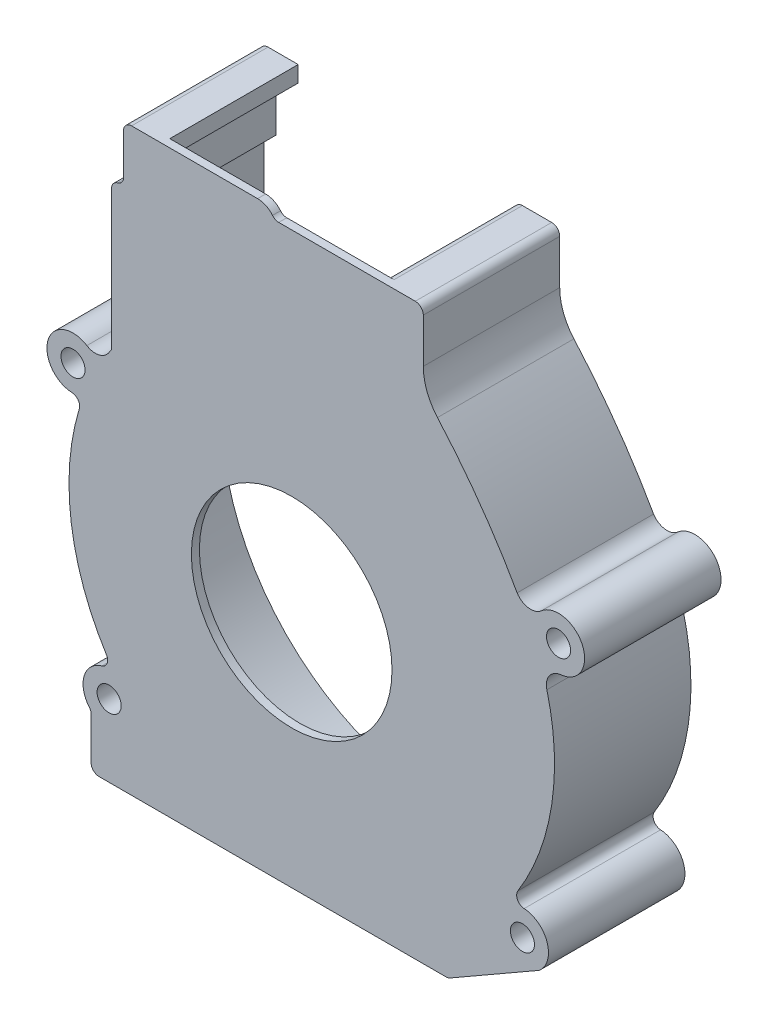
SolidWorks part; units mm, degrees
ref_plane "Front Plane" through (0, 0, 0) normal (0, 0, 1) x (1, 0, 0)
ref_plane "Top Plane" through (0, 0, 0) normal (0, 1, 0) x (1, 0, 0)
ref_plane "Right Plane" through (0, 0, 0) normal (1, 0, 0) x (0, 0, -1)
sketch "Sketch1" plane through (0, 0, 0) normal (0, 0, 1) x (1, 0, 0)
  line L0 (0, 0) -> (-5, 0) construction
  line L1 (-5, 0) -> (-5, 26.5) construction
  line L2 (-5, 26.5) -> (-5, 82.5) construction
  line L3 (-5, 26.5) -> (-59.5, 26.5) construction
  line L4 (-5, 26.5) -> (61.5, 26.5) construction
  line L5 (-5, 0) -> (-5, -41.5) construction
  line L6 (-5, -41.5) -> (-50.5, -41.5) construction
  line L7 (-5, -41.5) -> (52.5, -41.5) construction
  line L8 (-5, -41.5) -> (-5, -59.5) construction
  line L9 (-5, -59.5) -> (33.4669, -59.5)
  line L10 (34.4624, -59.2347) -> (56.6538, -46.4996)
  line L11 (-5, -59.5) -> (-53, -59.5)
  line L12 (-55, -57.5) -> (-55, -46.9772)
  line L13 (-49.8999, 69) -> (-49.8999, 34.2089)
  line L14 (-47.8999, 71) -> (-46.8999, 71)
  line L15 (-49.8999, 26.5) -> (-49.8999, 71) construction
  line L16 (-46.8999, 71) -> (-46.8999, 83)
  line L17 (-44.8999, 85) -> (-13.5, 85)
  line L18 (-5, 82.5) -> (-9.2869, 82.5) construction
  line L19 (-5, 82.5) -> (-3.5, 82.5)
  line L20 (-3.5, 82.5) -> (-3.5, 78.5)
  line L21 (-3.5, 78.5) -> (-5, 78.5)
  line L22 (-3.5, 82.5) -> (16.5, 82.5) construction
  line L23 (16.5, 80.5) -> (16.5, 78.5)
  line L24 (18.5, 82.5) -> (25.8, 82.5)
  line L25 (27.8, 80.5) -> (27.8, 69.4429)
  line L26 (0, 0) -> (51.1848, 32.2548) construction
  line L27 (16.5, 78.5) -> (21.8, 78.5)
  line L28 (23.8, 76.5) -> (23.8, 66.8106)
  line L29 (-8.2322, 82.5) -> (-5, 82.5)
  line L30 (-5, 80.2) -> (-23.0787, 80.2) construction
  line L31 (-13.5, 85) -> (-13.5, 76.5) construction
  line L32 (-40.8999, 81) -> (-20.1933, 81)
  line L33 (-42.8999, 79) -> (-42.8999, 67)
  line L34 (-42.8999, 67) -> (-43.8999, 67)
  line L35 (-45.8999, 65) -> (-45.8999, 46.8172)
  line L36 (-5, 78.5) -> (-7.7947, 78.5)
  line L37 (-5, 46.2) -> (-32.524, 46.2) construction
  arc A0 (-39.1968, 40.6922) -> (47.8006, 30.1222) centre (0, 0) ccw
  circle A1 centre (52.5, -41.5) radius 3
  arc A3 (51.3679, -31.9623) -> (58.5982, 15.0501) centre (0, 0) ccw
  circle A4 centre (0, 0) radius 60.5 construction
  circle A5 centre (-50.5, -41.5) radius 3
  arc A6 (-52.3102, -35.2572) -> (-55.4706, -45.6885) centre (-50.5, -41.5) ccw
  arc A7 (-44.0227, -41.5) -> (-44, -41.524) centre (0, 0) ccw
  circle A8 centre (-59.5, 26.5) radius 3
  arc A9 (-44, -41.524) -> (-44, -41.5) centre (-50.5, -41.5) ccw
  arc A10 (54.721, -47.6088) -> (52.9329, -35.0144) centre (52.5, -41.5) ccw
  circle A11 centre (61.5, 26.5) radius 3
  arc A12 (-56.0461, 32.0064) -> (-59.7674, 20.0055) centre (-59.5, 26.5) ccw
  arc A13 (62.102, 20.0279) -> (57.2093, 31.3826) centre (61.5, 26.5) ccw
  arc A14 (-57.9345, 17.431) -> (-51.1755, -32.2695) centre (0, 0) ccw
  arc A15 (-38.5261, 46.6475) -> (-37.3763, 48.2045) centre (-41.0733, 49.7317) ccw
  arc A16 (-52.3102, -35.2572) -> (-51.1755, -32.2695) centre (-52.8672, -33.3363) ccw
  arc A17 (-55, -46.9772) -> (-55.4706, -45.6885) centre (-57, -46.9772) ccw
  arc A18 (-53, -59.5) -> (-55, -57.5) centre (-53, -57.5) cw
  arc A19 (33.4669, -59.5) -> (34.4624, -59.2347) centre (33.4669, -57.5) ccw
  arc A20 (52.9329, -35.0144) -> (51.3679, -31.9623) centre (53.066, -33.0189) cw
  arc A21 (-57.9345, 17.431) -> (-59.7674, 20.0055) centre (-59.8497, 18.0072) ccw
  arc A22 (62.102, 20.0279) -> (58.5982, 15.0501) centre (62.4724, 16.0451) ccw
  arc A23 (57.2093, 31.3826) -> (51.1848, 32.2548) centre (54.5689, 34.3873) cw
  arc A24 (-50.5768, 33.2) -> (-56.0461, 32.0064) centre (-53.9207, 35.395) cw
  arc A25 (31.3271, 60.1522) -> (51.1848, 32.2548) centre (-88.5559, -46.1979) cw
  arc A26 (27.5522, 57.2722) -> (33.7188, 50.2324) centre (-85.9348, -48.3593) cw
  arc A27 (31.3271, 60.1522) -> (27.8, 69.4429) centre (41.8, 69.4429) cw
  arc A28 (27.5522, 57.2722) -> (23.8, 66.8106) centre (37.8, 66.8106) cw
  arc A29 (16.5, 80.5) -> (18.5, 82.5) centre (18.5, 80.5) cw
  arc A30 (23.8, 76.5) -> (21.8, 78.5) centre (21.8, 76.5) ccw
  arc A31 (27.8, 80.5) -> (25.8, 82.5) centre (25.8, 80.5) ccw
  arc A32 (-18.2247, 79.3529) -> (-9.4728, 77.5882) centre (-13.5, 80.2) ccw
  circle A33 centre (-13.5, 80.2) radius 3
  arc A34 (-46.8999, 83) -> (-44.8999, 85) centre (-44.8999, 83) cw
  arc A35 (-42.8999, 79) -> (-40.8999, 81) centre (-40.8999, 79) cw
  arc A36 (-45.8999, 65) -> (-43.8999, 67) centre (-43.8999, 65) cw
  arc A37 (-49.8999, 69) -> (-47.8999, 71) centre (-47.8999, 69) cw
  arc A38 (-18.2247, 79.3529) -> (-20.1933, 81) centre (-20.1933, 79) ccw
  arc A39 (-9.7815, 83.2353) -> (-13.5, 85) centre (-13.5, 80.2) ccw
  arc A40 (-9.7815, 83.2353) -> (-8.2322, 82.5) centre (-8.2322, 84.5) ccw
  arc A41 (-9.4728, 77.5882) -> (-7.7947, 78.5) centre (-7.7947, 76.5) cw
  circle A42 centre (-32.524, 46.2) radius 3
  arc A43 (-34.7363, 41.4389) -> (-37.3763, 48.2045) centre (-32.524, 46.2) ccw
  circle A44 centre (0, 0) radius 56.5 construction
  arc A45 (-38.5261, 46.6475) -> (-40.8731, 44.6053) centre (0, 0) ccw
  arc A46 (33.7188, 50.2324) -> (47.8006, 30.1222) centre (-33.6599, -11.9339) cw
  arc A47 (-39.1968, 40.6922) -> (-34.7363, 41.4389) centre (-36.4218, 37.8114) cw
  arc A48 (-49.8999, 34.2089) -> (-50.5768, 33.2) centre (0, 0) ccw
  arc A49 (-45.8999, 46.8172) -> (-40.8731, 44.6053) centre (-42.8999, 46.8172) ccw
  circle A50 centre (-5, 0) radius 45 construction
  point P80 (27.8, 82.5)
  point P94 (-46.8999, 85)
  dimension "D1" = 113
  dimension "D5" = 45.5
  dimension "D7" = 4
  dimension "D8" = 2
  dimension "D9" = 2
  dimension "D18" = 4
  dimension "D19" = 4
  dimension "D20" = 4
  dimension "D22" = 14
  dimension "D23" = 2
  dimension "D26" = 4
  dimension "D13" = 4
  dimension "D29" = 2
  dimension "D30" = 2
  dimension "D31" = 2
  dimension "D33" = 4
  dimension "D34" = 3
  dimension "D2" = 5
  dimension "D3" = 26.5
  dimension "D4" = 56
  dimension "D6" = 57.5
  dimension "D10" = 44.5
  dimension "D11" = 14
  dimension "D12" = 3
  dimension "D14" = 1.5
  dimension "D15" = 4
  dimension "D16" = 20
  dimension "D17" = 11.3
  dimension "D21" = 4
  dimension "D24" = 2.3
  dimension "D25" = 8.5
  dimension "D27" = 4
  dimension "D28" = 4
  dimension "D32" = 19.7
extrude "Boss-Extrude1" add sketch "Sketch1" along normal blind 32 contours A49 L35 A36 L34 L33 A35 L32 A38 A32 A41 L36 L21 L20 L19 L29 A40 A39 L17 A34 L16 L14 A37 L13 A48 A24 A12 A21 A14 A16 A6 A17 L12 A18 L11 L9 A19 L10 A10 A20 A3 A22 A13 A23 A25 A27 L25 A31 L24 A29 L23
sketch "Sketch2" plane through (0, 0, 32) normal (0, 0, 1) x (1, 0, 0)
  line L0 (-3.5, 82.5) -> (18.5, 82.5)
  line L1 (-3.5, 82.5) -> (16.5, 82.5) construction
  line L19 (-45.8999, 46.8172) -> (-45.8999, 65)
  line L20 (-43.8999, 67) -> (-42.8999, 67)
  line L21 (-42.8999, 67) -> (-42.8999, 79)
  line L22 (-40.8999, 81) -> (-20.1933, 81)
  line L23 (-7.7947, 78.5) -> (-3.5, 78.5)
  line L24 (-3.5, 78.5) -> (-3.5, 82.5)
  line L25 (-3.5, 82.5) -> (-8.2322, 82.5)
  line L26 (-13.5, 85) -> (-44.8999, 85)
  line L27 (-46.8999, 83) -> (-46.8999, 71)
  line L28 (-46.8999, 71) -> (-47.8999, 71)
  line L29 (-49.8999, 69) -> (-49.8999, 34.2089)
  line L30 (-55, -46.9772) -> (-55, -57.5)
  line L31 (-53, -59.5) -> (33.4669, -59.5)
  line L32 (34.4624, -59.2347) -> (56.6538, -46.4996)
  line L33 (27.8, 69.4429) -> (27.8, 80.5)
  line L34 (25.8, 82.5) -> (18.5, 82.5)
  line L35 (16.5, 80.5) -> (16.5, 78.5)
  line L36 (16.5, 78.5) -> (21.8, 78.5)
  line L37 (23.8, 76.5) -> (23.8, 66.8106)
  line L44 (-3.5, 82.5) -> (-8.2322, 82.5)
  line L45 (-13.5, 85) -> (-44.8999, 85)
  line L46 (-46.8999, 83) -> (-46.8999, 71)
  line L47 (-46.8999, 71) -> (-47.8999, 71)
  line L48 (-49.8999, 69) -> (-49.8999, 34.2089)
  line L49 (-55, -46.9772) -> (-55, -57.5)
  line L50 (-53, -59.5) -> (33.4669, -59.5)
  line L51 (34.4624, -59.2347) -> (56.6538, -46.4996)
  line L52 (27.8, 69.4429) -> (27.8, 80.5)
  line L53 (25.8, 82.5) -> (18.5, 82.5)
  circle A0 centre (61.5, 26.5) radius 3 construction
  circle A1 centre (61.5, 26.5) radius 3
  circle A2 centre (52.5, -41.5) radius 3 construction
  circle A3 centre (-50.5, -41.5) radius 3 construction
  circle A4 centre (-59.5, 26.5) radius 3 construction
  circle A5 centre (-32.524, 46.2) radius 3 construction
  circle A6 centre (-13.5, 80.2) radius 3 construction
  circle A7 centre (52.5, -41.5) radius 3
  circle A8 centre (-50.5, -41.5) radius 3
  circle A9 centre (-59.5, 26.5) radius 3
  circle A10 centre (-32.524, 46.2) radius 3
  circle A11 centre (-13.5, 80.2) radius 3
  circle A12 centre (-5, 0) radius 25
  arc A39 (-45.8999, 46.8172) -> (-40.8731, 44.6053) centre (-42.8999, 46.8172) ccw
  arc A40 (-43.8999, 67) -> (-45.8999, 65) centre (-43.8999, 65) ccw
  arc A41 (-40.8999, 81) -> (-42.8999, 79) centre (-40.8999, 79) ccw
  arc A42 (-18.2247, 79.3529) -> (-20.1933, 81) centre (-20.1933, 79) ccw
  arc A43 (-18.2247, 79.3529) -> (-9.4728, 77.5882) centre (-13.5, 80.2) ccw
  arc A44 (-7.7947, 78.5) -> (-9.4728, 77.5882) centre (-7.7947, 76.5) ccw
  arc A45 (-9.7815, 83.2353) -> (-8.2322, 82.5) centre (-8.2322, 84.5) ccw
  arc A46 (-9.7815, 83.2353) -> (-13.5, 85) centre (-13.5, 80.2) ccw
  arc A47 (-44.8999, 85) -> (-46.8999, 83) centre (-44.8999, 83) ccw
  arc A48 (-47.8999, 71) -> (-49.8999, 69) centre (-47.8999, 69) ccw
  arc A49 (-49.8999, 34.2089) -> (-50.5768, 33.2) centre (0, 0) ccw
  arc A50 (-56.0461, 32.0064) -> (-50.5768, 33.2) centre (-53.9207, 35.395) ccw
  arc A51 (-56.0461, 32.0064) -> (-59.7674, 20.0055) centre (-59.5, 26.5) ccw
  arc A52 (-57.9345, 17.431) -> (-59.7674, 20.0055) centre (-59.8497, 18.0072) ccw
  arc A53 (-57.9345, 17.431) -> (-51.1755, -32.2695) centre (0, 0) ccw
  arc A54 (-52.3102, -35.2572) -> (-51.1755, -32.2695) centre (-52.8672, -33.3363) ccw
  arc A55 (-52.3102, -35.2572) -> (-55.4706, -45.6885) centre (-50.5, -41.5) ccw
  arc A56 (-55, -46.9772) -> (-55.4706, -45.6885) centre (-57, -46.9772) ccw
  arc A57 (-55, -57.5) -> (-53, -59.5) centre (-53, -57.5) ccw
  arc A58 (33.4669, -59.5) -> (34.4624, -59.2347) centre (33.4669, -57.5) ccw
  arc A59 (56.6538, -46.4996) -> (52.9329, -35.0144) centre (52.5, -41.5) ccw
  arc A60 (51.3679, -31.9623) -> (52.9329, -35.0144) centre (53.066, -33.0189) ccw
  arc A61 (51.3679, -31.9623) -> (58.5982, 15.0501) centre (0, 0) ccw
  arc A62 (62.102, 20.0279) -> (58.5982, 15.0501) centre (62.4724, 16.0451) ccw
  arc A63 (62.102, 20.0279) -> (57.2093, 31.3826) centre (61.5, 26.5) ccw
  arc A64 (51.1848, 32.2548) -> (57.2093, 31.3826) centre (54.5689, 34.3873) ccw
  arc A65 (51.1848, 32.2548) -> (31.3271, 60.1522) centre (-88.5559, -46.1979) ccw
  arc A66 (27.8, 69.4429) -> (31.3271, 60.1522) centre (41.8, 69.4429) ccw
  arc A67 (27.8, 80.5) -> (25.8, 82.5) centre (25.8, 80.5) ccw
  arc A68 (18.5, 82.5) -> (16.5, 80.5) centre (18.5, 80.5) ccw
  arc A69 (23.8, 76.5) -> (21.8, 78.5) centre (21.8, 76.5) ccw
  arc A70 (23.8, 66.8106) -> (27.5522, 57.2722) centre (37.8, 66.8106) ccw
  arc A71 (33.7188, 50.2324) -> (27.5522, 57.2722) centre (-85.9348, -48.3593) ccw
  arc A72 (47.8006, 30.1222) -> (33.7188, 50.2324) centre (-33.6599, -11.9339) ccw
  arc A73 (-39.1968, 40.6922) -> (47.8006, 30.1222) centre (0, 0) ccw
  arc A74 (-34.7363, 41.4389) -> (-39.1968, 40.6922) centre (-36.4218, 37.8114) ccw
  arc A75 (-34.7363, 41.4389) -> (-37.3763, 48.2045) centre (-32.524, 46.2) ccw
  arc A76 (-38.5261, 46.6475) -> (-37.3763, 48.2045) centre (-41.0733, 49.7317) ccw
  arc A77 (-38.5261, 46.6475) -> (-40.8731, 44.6053) centre (0, 0) ccw
  arc A84 (-9.7815, 83.2353) -> (-8.2322, 82.5) centre (-8.2322, 84.5) ccw
  arc A85 (-9.7815, 83.2353) -> (-13.5, 85) centre (-13.5, 80.2) ccw
  arc A86 (-44.8999, 85) -> (-46.8999, 83) centre (-44.8999, 83) ccw
  arc A87 (-47.8999, 71) -> (-49.8999, 69) centre (-47.8999, 69) ccw
  arc A88 (-49.8999, 34.2089) -> (-50.5768, 33.2) centre (0, 0) ccw
  arc A89 (-56.0461, 32.0064) -> (-50.5768, 33.2) centre (-53.9207, 35.395) ccw
  arc A90 (-56.0461, 32.0064) -> (-59.7674, 20.0055) centre (-59.5, 26.5) ccw
  arc A91 (-57.9345, 17.431) -> (-59.7674, 20.0055) centre (-59.8497, 18.0072) ccw
  arc A92 (-57.9345, 17.431) -> (-51.1755, -32.2695) centre (0, 0) ccw
  arc A93 (-52.3102, -35.2572) -> (-51.1755, -32.2695) centre (-52.8672, -33.3363) ccw
  arc A94 (-52.3102, -35.2572) -> (-55.4706, -45.6885) centre (-50.5, -41.5) ccw
  arc A95 (-55, -46.9772) -> (-55.4706, -45.6885) centre (-57, -46.9772) ccw
  arc A96 (-55, -57.5) -> (-53, -59.5) centre (-53, -57.5) ccw
  arc A97 (33.4669, -59.5) -> (34.4624, -59.2347) centre (33.4669, -57.5) ccw
  arc A98 (56.6538, -46.4996) -> (52.9329, -35.0144) centre (52.5, -41.5) ccw
  arc A99 (51.3679, -31.9623) -> (52.9329, -35.0144) centre (53.066, -33.0189) ccw
  arc A100 (51.3679, -31.9623) -> (58.5982, 15.0501) centre (0, 0) ccw
  arc A101 (62.102, 20.0279) -> (58.5982, 15.0501) centre (62.4724, 16.0451) ccw
  arc A102 (62.102, 20.0279) -> (57.2093, 31.3826) centre (61.5, 26.5) ccw
  arc A103 (51.1848, 32.2548) -> (57.2093, 31.3826) centre (54.5689, 34.3873) ccw
  arc A104 (51.1848, 32.2548) -> (31.3271, 60.1522) centre (-88.5559, -46.1979) ccw
  arc A105 (27.8, 69.4429) -> (31.3271, 60.1522) centre (41.8, 69.4429) ccw
  arc A106 (27.8, 80.5) -> (25.8, 82.5) centre (25.8, 80.5) ccw
  arc A115 (-38.5261, 46.6475) -> (-37.3763, 48.2045) centre (-41.0733, 49.7317) ccw
  dimension "D1" = 0
extrude "Boss-Extrude2" add sketch "Sketch2" along normal blind 2
sketch "Sketch3" plane through (0, 0, 34) normal (0, 0, 1) x (1, 0, 0)
  line L0 (-3.5, 82.5) -> (16.5, 82.5) construction
  line L1 (-5, 82.5) -> (-3.5, 82.5) construction
  line L2 (-8.2322, 82.5) -> (-5, 82.5) construction
  line L3 (-44.8999, 85) -> (-13.5, 85) construction
  line L7 (-3.5, 82.5) -> (16.5, 82.5)
  line L8 (-5, 82.5) -> (-3.5, 82.5)
  line L9 (-8.2322, 82.5) -> (-5, 82.5)
  line L10 (-37.3763, 85) -> (-13.5, 85)
  line L14 (16.5, 82.5) -> (16.5, 46.4817)
  line L15 (13.5184, 43.4817) -> (-22.5293, 43.2611)
  line L16 (-40.8483, 43.8791) -> (-45.8999, 48.1905)
  line L17 (-40.8999, 81) -> (-20.1933, 81) construction
  line L18 (-42.8999, 79) -> (-42.8999, 67) construction
  line L19 (-42.8999, 67) -> (-43.8999, 67) construction
  line L20 (-45.8999, 65) -> (-45.8999, 46.8172) construction
  line L21 (-40.8999, 81) -> (-37.3763, 81)
  line L22 (-42.8999, 79) -> (-42.8999, 67)
  line L23 (-42.8999, 67) -> (-43.8999, 67)
  line L24 (-45.8999, 65) -> (-45.8999, 48.1905)
  line L25 (-37.3763, 81) -> (-37.3763, 85)
  arc A0 (-9.7815, 83.2353) -> (-8.2322, 82.5) centre (-8.2322, 84.5) ccw construction
  arc A1 (-9.7815, 83.2353) -> (-13.5, 85) centre (-13.5, 80.2) ccw construction
  arc A4 (-9.7815, 83.2353) -> (-8.2322, 82.5) centre (-8.2322, 84.5) ccw
  arc A5 (-9.7815, 83.2353) -> (-13.5, 85) centre (-13.5, 80.2) ccw
  arc A10 (16.5, 46.4817) -> (13.5184, 43.4817) centre (13.5, 46.4817) cw
  arc A11 (-40.8483, 43.8791) -> (-25.0912, 41.7916) centre (-32.524, 46.2) ccw
  arc A12 (-25.0912, 41.7916) -> (-22.5293, 43.2611) centre (-22.5109, 40.2612) cw
  arc A13 (-40.8999, 81) -> (-42.8999, 79) centre (-40.8999, 79) ccw construction
  arc A14 (-43.8999, 67) -> (-45.8999, 65) centre (-43.8999, 65) ccw construction
  arc A15 (-40.8999, 81) -> (-42.8999, 79) centre (-40.8999, 79) ccw
  arc A16 (-43.8999, 67) -> (-45.8999, 65) centre (-43.8999, 65) ccw
  point P20 (-39.9989, 43.1542)
  point P26 (16.5, 43.5)
  point P30 (-42.8999, 67)
  point P32 (-43.8999, 67)
  dimension "D4" = 3
  dimension "D1" = 39
  dimension "D2" = 56.4989
extrude "Cut-Extrude3" cut sketch "Sketch3" against normal blind 43.5
sketch "Sketch5" plane through (0, 0, 34) normal (0, 0, 1) x (1, 0, 0)
  line L0 (-3.5, 82.5) -> (16.5, 82.5) construction
  line L1 (-5, 82.5) -> (-3.5, 82.5) construction
  line L2 (-8.2322, 82.5) -> (-5, 82.5) construction
  line L3 (-44.8999, 85) -> (-13.5, 85) construction
  line L4 (-40.8999, 81) -> (-20.1933, 81) construction
  line L5 (16.5, 46.4817) -> (16.5, 82.5) construction
  line L6 (-22.5293, 43.2611) -> (13.5184, 43.4817) construction
  line L7 (-45.8999, 48.1905) -> (-40.8483, 43.8791) construction
  line L8 (-45.8999, 65) -> (-45.8999, 46.8172) construction
  line L9 (-42.8999, 67) -> (-43.8999, 67) construction
  line L10 (-42.8999, 79) -> (-42.8999, 67) construction
  line L11 (-37.3763, 85) -> (-37.3763, 81) construction
  line L12 (-3.5, 82.5) -> (16.5, 82.5)
  line L13 (-5, 82.5) -> (-3.5, 82.5)
  line L14 (-8.2322, 82.5) -> (-5, 82.5)
  line L15 (-37.3763, 85) -> (-13.5, 85)
  line L16 (-40.8999, 81) -> (-37.3763, 81)
  line L17 (16.5, 46.4817) -> (16.5, 82.5)
  line L18 (-22.5293, 43.2611) -> (13.5184, 43.4817)
  line L19 (-45.8999, 48.1905) -> (-40.8483, 43.8791)
  line L20 (-45.8999, 65) -> (-45.8999, 48.1905)
  line L21 (-42.8999, 67) -> (-43.8999, 67)
  line L22 (-42.8999, 79) -> (-42.8999, 67)
  line L23 (-37.3763, 85) -> (-37.3763, 81)
  arc A0 (-9.7815, 83.2353) -> (-8.2322, 82.5) centre (-8.2322, 84.5) ccw construction
  arc A1 (-9.7815, 83.2353) -> (-13.5, 85) centre (-13.5, 80.2) ccw construction
  arc A2 (13.5184, 43.4817) -> (16.5, 46.4817) centre (13.5, 46.4817) ccw construction
  arc A3 (-22.5293, 43.2611) -> (-25.0912, 41.7916) centre (-22.5109, 40.2612) ccw construction
  arc A4 (-40.8483, 43.8791) -> (-25.0912, 41.7916) centre (-32.524, 46.2) ccw construction
  arc A5 (-43.8999, 67) -> (-45.8999, 65) centre (-43.8999, 65) ccw construction
  arc A6 (-40.8999, 81) -> (-42.8999, 79) centre (-40.8999, 79) ccw construction
  arc A7 (-9.7815, 83.2353) -> (-8.2322, 82.5) centre (-8.2322, 84.5) ccw
  arc A8 (-9.7815, 83.2353) -> (-13.5, 85) centre (-13.5, 80.2) ccw
  arc A9 (13.5184, 43.4817) -> (16.5, 46.4817) centre (13.5, 46.4817) ccw
  arc A10 (-22.5293, 43.2611) -> (-25.0912, 41.7916) centre (-22.5109, 40.2612) ccw
  arc A11 (-40.8483, 43.8791) -> (-25.0912, 41.7916) centre (-32.524, 46.2) ccw
  arc A12 (-43.8999, 67) -> (-45.8999, 65) centre (-43.8999, 65) ccw
  arc A13 (-40.8999, 81) -> (-42.8999, 79) centre (-40.8999, 79) ccw
extrude "Boss-Extrude3" add sketch "Sketch5" against normal blind 2
fillet "Fillet3" radius 2 1 edges at (-46.8999, 71, 17)
